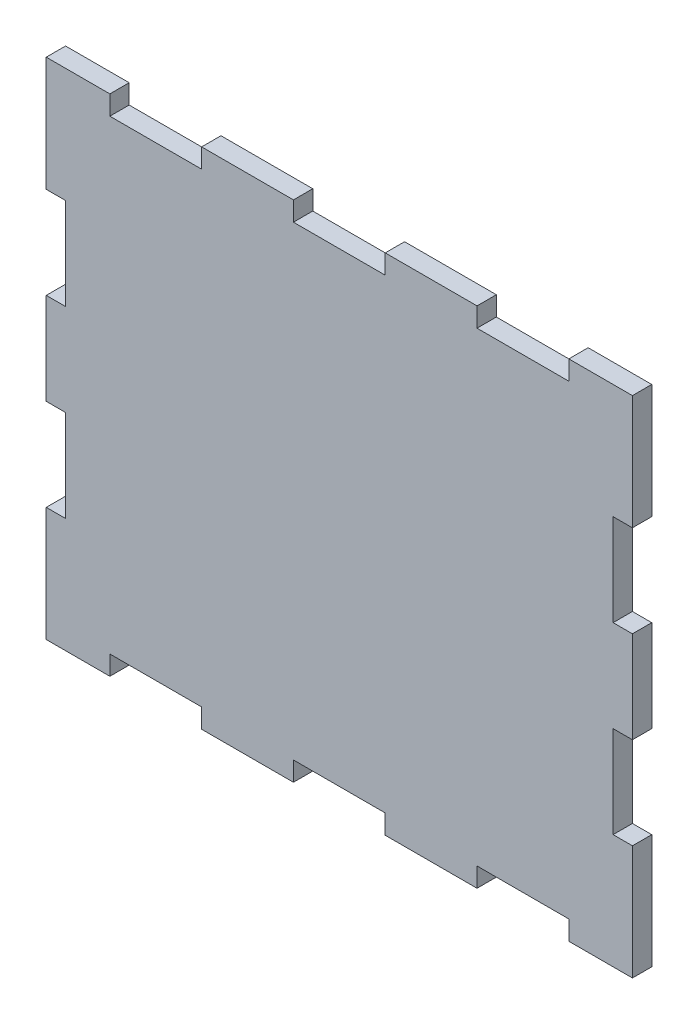
SolidWorks part; units mm, degrees
ref_plane "Front Plane" through (0, 0, 0) normal (0, 0, 1) x (1, 0, 0)
ref_plane "Top Plane" through (0, 0, 0) normal (0, 1, 0) x (1, 0, 0)
ref_plane "Right Plane" through (0, 0, 0) normal (1, 0, 0) x (0, 0, -1)
sketch "Sketch1" plane through (0, 0, 0) normal (0, 0, 1) x (1, 0, 0)
  line L54 (-43.1592, 37.3294) -> (-43.1592, 19.5544)
  line L55 (-43.1592, 19.5544) -> (-40.1592, 19.5544)
  line L56 (-40.1592, 19.5544) -> (-40.1592, 5.3044)
  line L57 (-40.1592, 5.3044) -> (-43.1592, 5.3044)
  line L58 (-43.1592, 5.3044) -> (-43.1592, -8.9456)
  line L59 (-43.1592, -8.9456) -> (-40.1592, -8.9456)
  line L60 (-40.1592, -8.9456) -> (-40.1592, -23.1956)
  line L61 (-40.1592, -23.1956) -> (-43.1592, -23.1956)
  line L62 (-43.1592, -23.1956) -> (-43.1592, -37.4456)
  line L63 (-43.1592, -37.4456) -> (-43.1592, -40.9706)
  line L64 (-43.1592, -40.9706) -> (-33.2842, -40.9706)
  line L65 (-33.2842, -40.9706) -> (-33.2842, -37.9706)
  line L66 (-33.2842, -37.9706) -> (-19.0342, -37.9706)
  line L67 (-19.0342, -37.9706) -> (-19.0342, -40.9706)
  line L68 (-19.0342, -40.9706) -> (-4.7842, -40.9706)
  line L69 (-4.7842, -40.9706) -> (-4.7842, -37.9706)
  line L70 (-4.7842, -37.9706) -> (9.4658, -37.9706)
  line L71 (9.4658, -37.9706) -> (9.4658, -40.9706)
  line L72 (9.4658, -40.9706) -> (23.7158, -40.9706)
  line L73 (23.7158, -40.9706) -> (23.7158, -37.9706)
  line L74 (23.7158, -37.9706) -> (37.9658, -37.9706)
  line L75 (37.9658, -37.9706) -> (37.9658, -40.9706)
  line L76 (37.9658, -40.9706) -> (47.8408, -40.9706)
  line L77 (47.8408, -40.9706) -> (47.8408, -23.1956)
  line L78 (47.8408, -23.1956) -> (44.8408, -23.1956)
  line L79 (44.8408, -23.1956) -> (44.8408, -8.9456)
  line L80 (44.8408, -8.9456) -> (47.8408, -8.9456)
  line L81 (47.8408, -8.9456) -> (47.8408, 5.3044)
  line L82 (47.8408, 5.3044) -> (44.8408, 5.3044)
  line L83 (44.8408, 5.3044) -> (44.8408, 19.5544)
  line L84 (44.8408, 19.5544) -> (47.8408, 19.5544)
  line L85 (47.8408, 19.5544) -> (47.8408, 33.8044)
  line L86 (47.8408, 33.8044) -> (47.8408, 37.3294)
  line L87 (47.8408, 37.3294) -> (37.9658, 37.3294)
  line L88 (37.9658, 37.3294) -> (37.9658, 34.3294)
  line L89 (37.9658, 34.3294) -> (23.7158, 34.3294)
  line L90 (23.7158, 34.3294) -> (23.7158, 37.3294)
  line L91 (23.7158, 37.3294) -> (9.4658, 37.3294)
  line L92 (9.4658, 37.3294) -> (9.4658, 34.3294)
  line L93 (9.4658, 34.3294) -> (-4.7842, 34.3294)
  line L94 (-4.7842, 34.3294) -> (-4.7842, 37.3294)
  line L95 (-4.7842, 37.3294) -> (-19.0342, 37.3294)
  line L96 (-19.0342, 37.3294) -> (-19.0342, 34.3294)
  line L97 (-19.0342, 34.3294) -> (-33.2842, 34.3294)
  line L98 (-33.2842, 34.3294) -> (-33.2842, 37.3294)
  line L99 (-33.2842, 37.3294) -> (-43.1592, 37.3294)
extrude "Boss-Extrude1" add sketch "Sketch1" along normal blind 3
